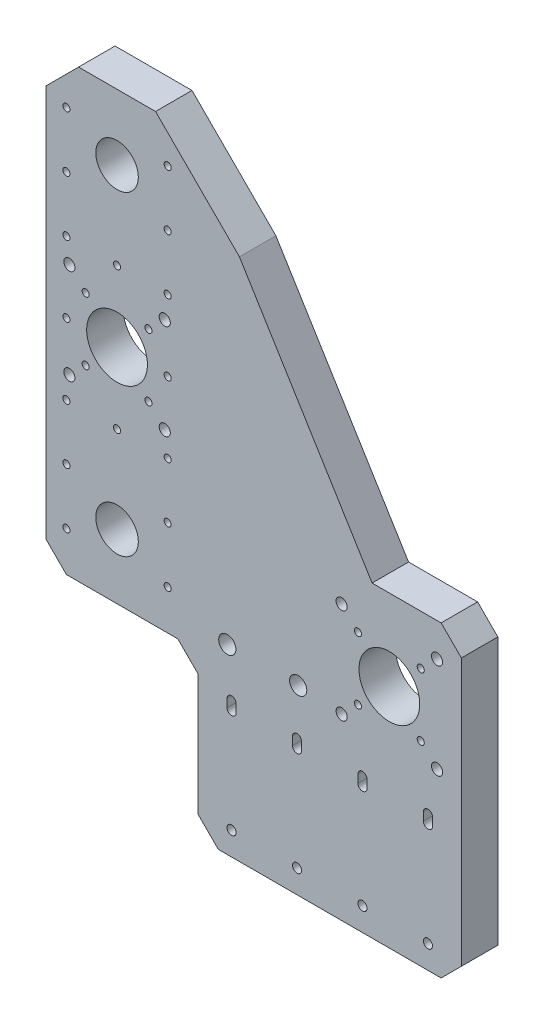
SolidWorks part; units mm, degrees
material "Beech"
ref_plane "Front Plane" through (0, 0, 0) normal (0, 0, 1) x (1, 0, 0)
ref_plane "Top Plane" through (0, 0, 0) normal (0, 1, 0) x (1, 0, 0)
ref_plane "Right Plane" through (0, 0, 0) normal (1, 0, 0) x (0, 0, -1)
sketch "Model" plane through (0, 0, 0) normal (0, 0, 1) x (1, 0, 0)
  line L0 (195, 0) -> (205, 10)
  line L1 (195, 0) -> (85, 0)
  line L2 (75, 10) -> (85, 0)
  line L3 (75, 10) -> (75, 70)
  line L4 (65, 80) -> (75, 70)
  line L5 (65, 80) -> (10, 80)
  line L6 (0, 90) -> (10, 80)
  line L7 (0, 90) -> (0, 284)
  line L8 (16, 300) -> (0, 284)
  line L9 (16, 300) -> (54, 300)
  line L10 (95.4118, 258.5882) -> (54, 300)
  line L11 (95.4118, 258.5882) -> (160.9225, 151.83)
  line L12 (195, 151.83) -> (160.9225, 151.83)
  line L13 (205, 141.83) -> (195, 151.83)
  line L14 (205, 141.83) -> (205, 10)
  line L15 (89.29, 66.7) -> (89.29, 62.7)
  line L16 (93.79, 62.7) -> (93.79, 66.7)
  line L17 (121.61, 66.7) -> (121.61, 62.7)
  line L18 (126.11, 62.7) -> (126.11, 66.7)
  line L19 (153.93, 66.7) -> (153.93, 62.7)
  line L20 (158.43, 62.7) -> (158.43, 66.7)
  line L21 (186.25, 66.7) -> (186.25, 62.7)
  line L22 (190.75, 62.7) -> (190.75, 66.7)
  line L23 (91.54, 66.7) -> (91.54, 11.5) construction
  line L24 (91.54, 11.5) -> (188.5, 11.5) construction
  line L25 (188.5, 11.5) -> (188.5, 66.7) construction
  line L26 (188.5, 66.7) -> (91.54, 66.7) construction
  line L27 (123.86, 11.5) -> (123.86, 66.7) construction
  line L28 (156.18, 11.5) -> (156.18, 66.7) construction
  line L29 (89.43, 89.83) -> (124.43, 89.83) construction
  line L30 (184.93, 127.33) -> (153.93, 127.33) construction
  line L31 (184.93, 127.33) -> (184.93, 96.33) construction
  line L32 (184.93, 96.33) -> (153.93, 96.33) construction
  line L33 (153.93, 127.33) -> (153.93, 96.33) construction
  line L34 (184.93, 127.33) -> (153.93, 96.33) construction
  line L35 (184.93, 96.33) -> (153.93, 127.33) construction
  line L36 (192.98, 135.38) -> (145.88, 135.38) construction
  line L37 (192.98, 135.38) -> (192.98, 88.28) construction
  line L38 (192.98, 88.28) -> (145.88, 88.28) construction
  line L39 (145.88, 135.38) -> (145.88, 88.28) construction
  line L40 (192.98, 135.38) -> (145.88, 88.28) construction
  line L41 (192.98, 88.28) -> (145.88, 135.38) construction
  line L42 (35, 267.61) -> (35, 111.81) construction
  line L43 (10, 99.7) -> (60, 99.7) construction
  line L44 (10, 99.7) -> (10, 127.2) construction
  line L45 (10, 127.2) -> (60, 127.2) construction
  line L46 (60, 99.7) -> (60, 127.2) construction
  line L47 (60, 127.2) -> (10, 127.2) construction
  line L48 (60, 127.2) -> (60, 154.7) construction
  line L49 (60, 154.7) -> (10, 154.7) construction
  line L50 (10, 127.2) -> (10, 154.7) construction
  line L51 (10, 154.7) -> (60, 154.7) construction
  line L52 (10, 154.7) -> (10, 189.7) construction
  line L53 (10, 189.7) -> (60, 189.7) construction
  line L54 (60, 154.7) -> (60, 189.7) construction
  line L55 (10, 189.7) -> (60, 189.7) construction
  line L56 (10, 189.7) -> (10, 224.7) construction
  line L57 (10, 224.7) -> (60, 224.7) construction
  line L58 (60, 189.7) -> (60, 224.7) construction
  line L59 (10, 224.7) -> (60, 224.7) construction
  line L60 (10, 224.7) -> (10, 252.2) construction
  line L61 (10, 252.2) -> (60, 252.2) construction
  line L62 (60, 224.7) -> (60, 252.2) construction
  line L63 (10, 252.2) -> (60, 252.2) construction
  line L64 (10, 252.2) -> (10, 279.7) construction
  line L65 (10, 279.7) -> (60, 279.7) construction
  line L66 (60, 252.2) -> (60, 279.7) construction
  line L67 (91.54, 62.7) -> (188.5, 62.7) construction
  line L68 (50.5, 205.2) -> (19.5, 205.2) construction
  line L69 (50.5, 205.2) -> (50.5, 174.2) construction
  line L70 (50.5, 174.2) -> (19.5, 174.2) construction
  line L71 (19.5, 205.2) -> (19.5, 174.2) construction
  line L72 (50.5, 205.2) -> (19.5, 174.2) construction
  line L73 (50.5, 174.2) -> (19.5, 205.2) construction
  line L74 (58.55, 213.25) -> (11.45, 213.25) construction
  line L75 (58.55, 213.25) -> (58.55, 166.15) construction
  line L76 (58.55, 166.15) -> (11.45, 166.15) construction
  line L77 (11.45, 213.25) -> (11.45, 166.15) construction
  line L78 (58.55, 213.25) -> (11.45, 166.15) construction
  line L79 (58.55, 166.15) -> (11.45, 213.25) construction
  line L80 (0, 90) -> (0, 0) construction
  line L81 (85, 0) -> (0, 0) construction
  circle A0 centre (60, 279.7) radius 1.75
  circle A1 centre (10, 279.7) radius 1.75
  circle A2 centre (10, 224.7) radius 1.75
  circle A3 centre (10, 154.7) radius 1.75
  circle A4 centre (10, 99.7) radius 1.75
  circle A5 centre (60, 99.7) radius 1.75
  circle A6 centre (60, 154.7) radius 1.75
  circle A7 centre (60, 224.7) radius 1.75
  circle A8 centre (10, 252.2) radius 1.75
  circle A9 centre (60, 252.2) radius 1.75
  circle A10 centre (35, 224.7) radius 1.75
  circle A11 centre (10, 189.7) radius 1.75
  circle A12 centre (60, 189.7) radius 1.75
  circle A13 centre (10, 127.2) radius 1.75
  circle A14 centre (60, 127.2) radius 1.75
  circle A15 centre (35, 154.7) radius 1.75
  circle A16 centre (91.54, 11.5) radius 2.25
  circle A17 centre (123.86, 11.5) radius 2.25
  circle A18 centre (156.18, 11.5) radius 2.25
  circle A19 centre (188.5, 11.5) radius 2.25
  circle A20 centre (50.5, 205.2) radius 1.75
  circle A21 centre (50.5, 174.2) radius 1.75
  circle A22 centre (35, 189.7) radius 15
  circle A23 centre (19.5, 174.2) radius 1.75
  circle A24 centre (19.5, 205.2) radius 1.75
  circle A25 centre (11.45, 213.25) radius 2.75
  circle A26 centre (58.55, 213.25) radius 2.75
  circle A27 centre (58.55, 166.15) radius 2.75
  circle A28 centre (11.45, 166.15) radius 2.75
  circle A29 centre (35, 111.81) radius 10.5
  circle A30 centre (35, 267.61) radius 10.5
  circle A31 centre (89.43, 89.83) radius 4.25
  circle A32 centre (124.43, 89.83) radius 4.25
  circle A33 centre (145.88, 135.38) radius 2.75
  circle A34 centre (192.98, 135.38) radius 2.75
  circle A35 centre (192.98, 88.28) radius 2.75
  circle A36 centre (145.88, 88.28) radius 2.75
  circle A37 centre (169.43, 111.83) radius 15
  circle A38 centre (153.93, 96.33) radius 1.75
  circle A39 centre (184.93, 127.33) radius 1.75
  circle A40 centre (184.93, 96.33) radius 1.75
  circle A41 centre (153.93, 127.33) radius 1.75
  arc A42 (93.79, 66.7) -> (89.29, 66.7) centre (91.54, 66.7) ccw
  arc A43 (89.29, 62.7) -> (93.79, 62.7) centre (91.54, 62.7) ccw
  arc A44 (126.11, 66.7) -> (121.61, 66.7) centre (123.86, 66.7) ccw
  arc A45 (121.61, 62.7) -> (126.11, 62.7) centre (123.86, 62.7) ccw
  arc A46 (158.43, 66.7) -> (153.93, 66.7) centre (156.18, 66.7) ccw
  arc A47 (153.93, 62.7) -> (158.43, 62.7) centre (156.18, 62.7) ccw
  arc A48 (190.75, 66.7) -> (186.25, 66.7) centre (188.5, 66.7) ccw
  arc A49 (186.25, 62.7) -> (190.75, 62.7) centre (188.5, 62.7) ccw
  dimension "D15" = 4.5
  dimension "D16" = 111.83
  dimension "D19" = 30
  dimension "D20" = 5.5
  dimension "D21" = 3.5
  dimension "D22" = 35
  dimension "D24" = 8.5
  dimension "D35" = 12.11
  dimension "D38" = 21
  dimension "D39" = 16
  dimension "D50" = 23.55
  dimension "D51" = 267.61
  dimension "D1" = 11.5
  dimension "D2" = 66.7
  dimension "D3" = 4
  dimension "D4" = 151.83
  dimension "D5" = 130
  dimension "D6" = 205
  dimension "D7" = 80
  dimension "D8" = 300
  dimension "D9" = 44.0775
  dimension "D10" = 89.43
  dimension "D11" = 32.32
  dimension "D12" = 32.32
  dimension "D13" = 32.32
  dimension "D14" = 16.5
  dimension "D17" = 31
  dimension "D18" = 47.1
  dimension "D23" = 89.83
  dimension "D25" = 99.7
  dimension "D26" = 27.5
  dimension "D27" = 27.5
  dimension "D28" = 35
  dimension "D29" = 35
  dimension "D30" = 10
  dimension "D31" = 27.5
  dimension "D32" = 27.5
  dimension "D33" = 50
  dimension "D34" = 25
  dimension "D36" = 47.1
  dimension "D37" = 31
  dimension "D40" = 16
  dimension "D41" = 41.4118
  dimension "D42" = 41.4118
  dimension "D43" = 38
  dimension "D44" = 10
  dimension "D45" = 10
  dimension "D46" = 10
  dimension "D47" = 10
  dimension "D48" = 10
  dimension "D49" = 10
extrude "Boss-Extrude1" add sketch "Model" along normal blind 18
